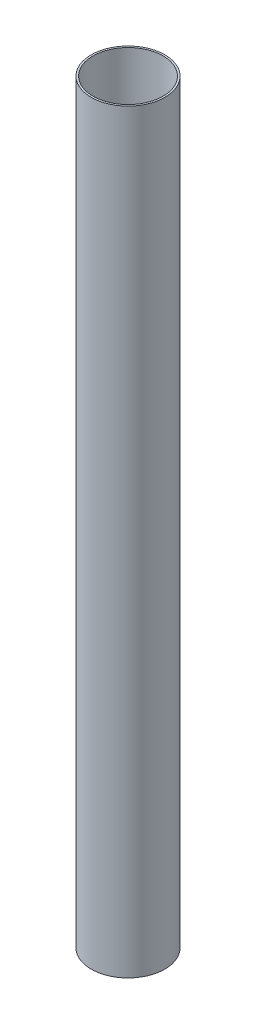
SolidWorks part; units mm, degrees
ref_plane "Front Plane" through (0, 0, 0) normal (0, 0, 1) x (1, 0, 0)
ref_plane "Top Plane" through (0, 0, 0) normal (0, 1, 0) x (1, 0, 0)
ref_plane "Right Plane" through (0, 0, 0) normal (1, 0, 0) x (0, 0, -1)
sketch "Sketch1" plane through (0, 0, 0) normal (0, 1, 0) x (1, 0, 0)
  circle A0 centre (0, 0) radius 40
  circle A1 centre (0, 0) radius 38
extrude "Boss-Extrude1" add sketch "Sketch1" along normal blind 820
